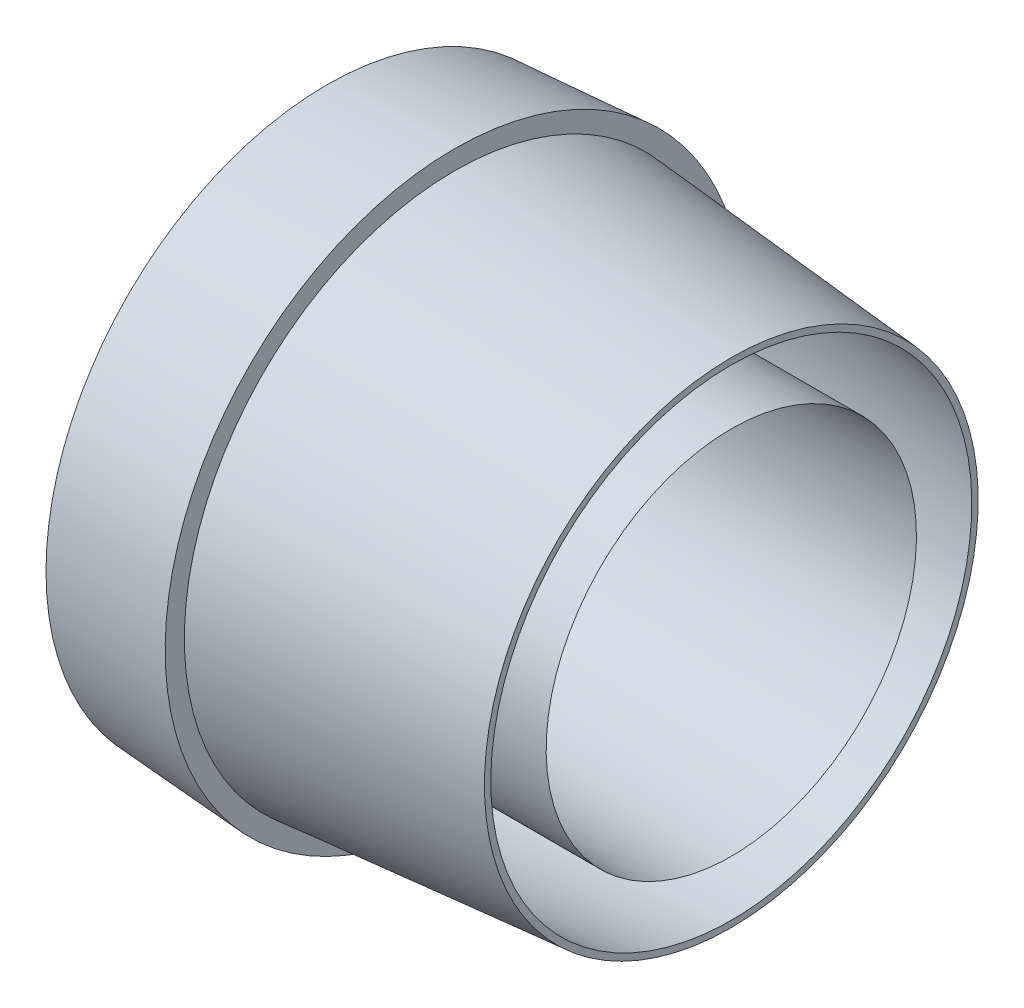
SolidWorks part; units mm, degrees
ref_plane "Front Plane" through (0, 0, 0) normal (0, 0, 1) x (1, 0, 0)
ref_plane "Top Plane" through (0, 0, 0) normal (0, 1, 0) x (1, 0, 0)
ref_plane "Right Plane" through (0, 0, 0) normal (1, 0, 0) x (0, 0, -1)
sketch "Sketch1" plane through (0, 0, 0) normal (0, 0, 1) x (1, 0, 0)
  line L0 (0, 0) -> (5000, 0) construction
  line L1 (3400, 350) -> (3400, 660)
  line L2 (3400, 660) -> (3700, 680)
  line L3 (3700, 680) -> (3700, 380)
  line L4 (3700, 380) -> (3400, 350)
revolve "Revolve1" add sketch "Sketch1" angle 360 about L0
sketch "Sketch2" plane through (0, 0, 0) normal (0, 0, 1) x (1, 0, 0)
  line L0 (0, 0) -> (5000, 0) construction
  line L1 (3700, 620) -> (3700, 635)
  line L2 (3700, -680) -> (3700, 680) construction
  line L3 (3700, 635) -> (4350, 580)
  line L4 (4350, 580) -> (4350, 565)
  line L5 (4350, 565) -> (3700, 620)
revolve "Revolve2" add sketch "Sketch2" angle 360 about L0
sketch "Sketch3" plane through (0, 0, 0) normal (0, 0, 1) x (1, 0, 0)
  line L0 (0, 0) -> (5000, 0) construction
  line L1 (3700, 420) -> (3700, 435)
  line L2 (3700, -680) -> (3700, 680) construction
  line L3 (3700, 435) -> (4350, 435)
  line L4 (4350, -580) -> (4350, 580) construction
  line L5 (4350, 435) -> (3700, 420)
revolve "Revolve3" add sketch "Sketch3" angle 360 about L0
